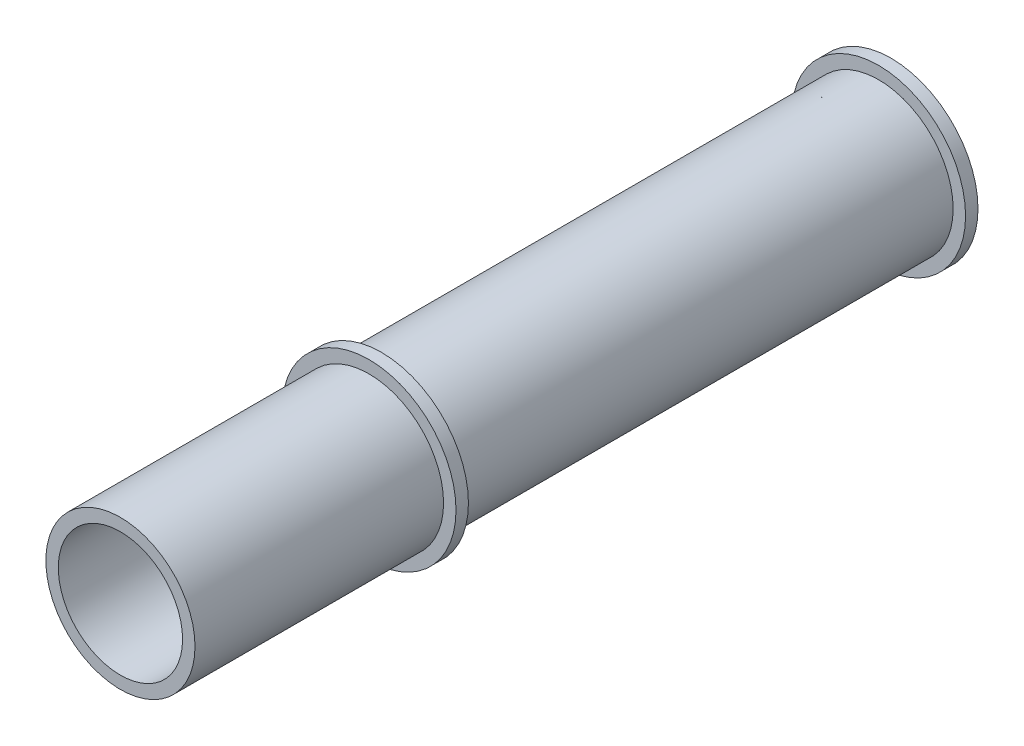
SolidWorks part; units mm, degrees
material "AISI Type 316L stainless steel"
ref_plane "Front Plane" through (0, 0, 0) normal (0, 0, 1) x (1, 0, 0)
ref_plane "Top Plane" through (0, 0, 0) normal (0, 1, 0) x (1, 0, 0)
ref_plane "Right Plane" through (0, 0, 0) normal (1, 0, 0) x (0, 0, -1)
sketch "Sketch1" plane through (0, 0, 0) normal (0, 0, 1) x (1, 0, 0)
  circle A0 centre (0, 0) radius 6
extrude "Boss-Extrude1" add sketch "Sketch1" along normal blind 40 contours A0
sketch "Sketch2" plane through (0, 0, 0) normal (0, 0, -1) x (-1, 0, 0)
  circle A0 centre (0, 0) radius 7
extrude "Boss-Extrude2" add sketch "Sketch2" along normal blind 1
sketch "Sketch3" plane through (0, 0, 40) normal (0, 0, 1) x (1, 0, 0)
  circle A0 centre (0, 0) radius 7
extrude "Boss-Extrude3" add sketch "Sketch3" along normal blind 1
sketch "Sketch4" plane through (0, 0, 41) normal (0, 0, 1) x (1, 0, 0)
  circle A0 centre (0, 0) radius 6
extrude "Boss-Extrude4" add sketch "Sketch4" along normal blind 20
sketch "Sketch5" plane through (0, 0, 61) normal (0, 0, 1) x (1, 0, 0)
  circle A0 centre (0, 0) radius 5
extrude "Cut-Extrude1" cut sketch "Sketch5" against normal blind 200
